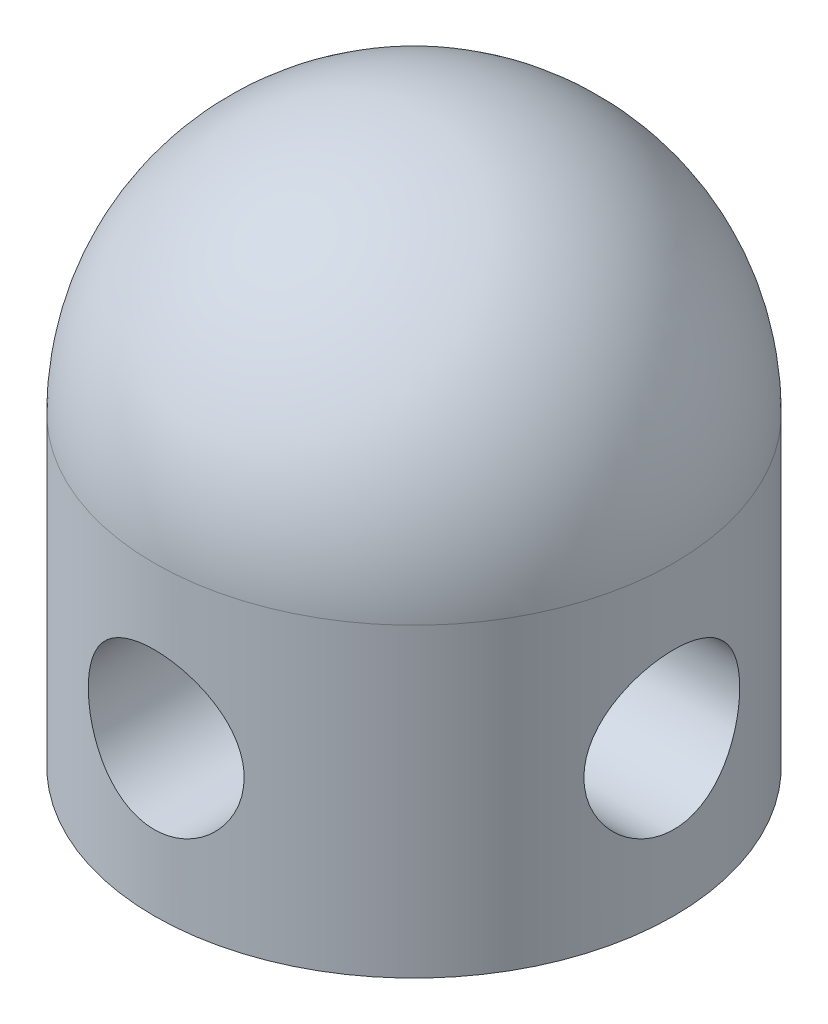
SolidWorks part; units mm, degrees
ref_plane "Front Plane" through (0, 0, 0) normal (0, 0, 1) x (1, 0, 0)
ref_plane "Top Plane" through (0, 0, 0) normal (0, 1, 0) x (1, 0, 0)
ref_plane "Right Plane" through (0, 0, 0) normal (1, 0, 0) x (0, 0, -1)
sketch "cirkel" plane through (0, 0, 0) normal (0, 1, 0) x (1, 0, 0)
  circle A0 centre (0, 0) radius 17
  dimension "D1" = 34
extrude "cilinder" add sketch "cirkel" along normal blind 20
sketch "boog" plane through (0, 0, 0) normal (0, 0, 1) x (1, 0, 0)
  line L0 (0, 20) -> (0, 37)
  line L1 (17, 20) -> (-17, 20) construction
  line L4 (0, 20) -> (-17, 20)
  arc A1 (-17, 20) -> (0, 37) centre (0, 20) cw
revolve "bol" add sketch "boog" angle 360 about L0
ref_plane "Plane1" through (0, 0, 17) normal (0, 0, 1) x (1, 0, 0)
sketch "cirkel_gat" plane through (0, 0, 17) normal (0, 0, 1) x (1, 0, 0)
  line L0 (-17, 0) -> (17, 0) construction
  line L1 (0, 0) -> (0, 10) construction
  circle A0 centre (0, 10) radius 5.1
  dimension "D1" = 10.2
  dimension "D2" = 10
extrude "opening" cut sketch "cirkel_gat" against normal blind 10 contours A0
pattern_circular "gaten_patroon" count 4 over 360 about axis through (0, 0, 0) along (0, 1, 0) of "opening"
sketch "cirkel1" plane through (0, 0, 0) normal (0, -1, 0) x (-1, 0, 0)
  circle A0 centre (0, 0) radius 13.5
  dimension "D1" = 27
extrude "opening_opzet" cut sketch "cirkel1" against normal blind 3
sketch "cirkel2" plane through (0, 3, 0) normal (0, -1, 0) x (-1, 0, 0)
  circle A0 centre (0, 0) radius 2
  dimension "D1" = 4
extrude "gat_verloopstuk" cut sketch "cirkel2" against normal blind 8
sketch "cirkel3" plane through (0, 3, 0) normal (0, -1, 0) x (1, 0, 0)
  circle A0 centre (0, 0) radius 3
  dimension "D1" = 6
extrude "gat_verloopstuk_rand" cut sketch "cirkel3" against normal blind 2
